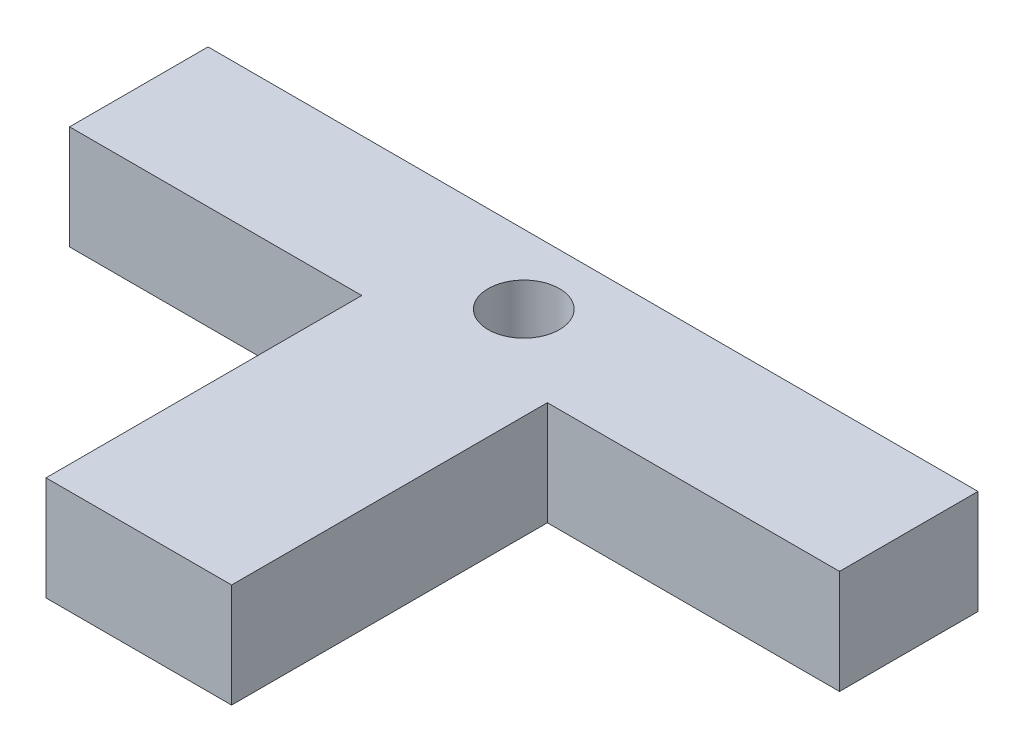
SolidWorks part; units mm, degrees
ref_plane "Front Plane" through (0, 0, 0) normal (0, 0, 1) x (1, 0, 0)
ref_plane "Top Plane" through (0, 0, 0) normal (0, 1, 0) x (1, 0, 0)
ref_plane "Right Plane" through (0, 0, 0) normal (1, 0, 0) x (0, 0, -1)
sketch "Sketch2" plane through (0, 0, 0) normal (0, 1, 0) x (1, 0, 0)
  line L0 (-55.5, -9.9811) -> (55.5, -9.9811)
  line L1 (-55.5, -9.9811) -> (-55.5, 9.9811)
  line L2 (-55.5, 9.9811) -> (55.5, 9.9811)
  line L3 (55.5, -9.9811) -> (55.5, 9.9811)
  line L4 (-55.5, -9.9811) -> (55.5, 9.9811) construction
  line L5 (-55.5, 9.9811) -> (55.5, -9.9811) construction
  line L6 (-13.3787, -9.9811) -> (13.3787, -9.9811)
  line L7 (-13.3787, -9.9811) -> (-13.3787, -55.5)
  line L8 (-13.3787, -55.5) -> (13.3787, -55.5)
  line L9 (13.3787, -9.9811) -> (13.3787, -55.5)
  circle A0 centre (0, 0) radius 5.135
  point P0 (0, 0)
  point P9 (0, -9.9811)
  point P10 (0, -55.5)
  point P16 (0, 0)
  dimension "D5" = 10.27
  dimension "D1" = 19.9621
  dimension "D2" = 26.7574
  dimension "D3" = 111
  dimension "D4" = 45.5189
extrude "Boss-Extrude1" add sketch "Sketch2" along normal blind 15 contours L0 L3 L2 L1 A0 | L9 L0 L7 L8
